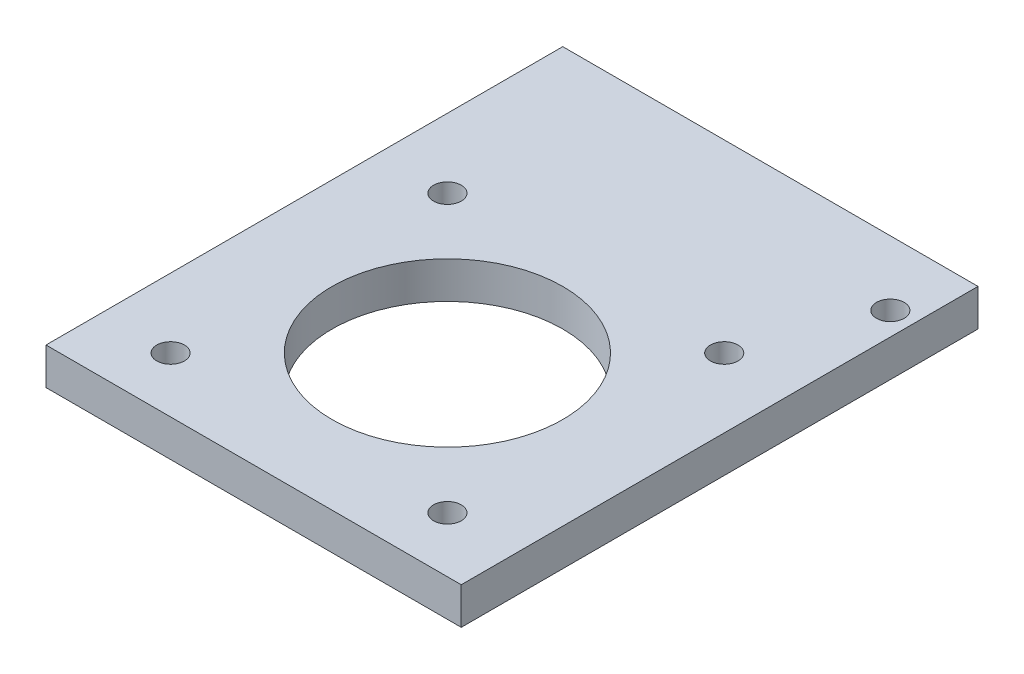
SolidWorks part; units mm, degrees
ref_plane "Plano frontal" through (0, 0, 0) normal (0, 0, 1) x (1, 0, 0)
ref_plane "Plano superior" through (0, 0, 0) normal (0, 1, 0) x (1, 0, 0)
ref_plane "Plano direito" through (0, 0, 0) normal (1, 0, 0) x (0, 0, -1)
sketch "Esboço1" plane through (0, 0, 0) normal (0, 1, 0) x (1, 0, 0)
  line L1 (-22.5, 28) -> (22.5, 28)
  line L2 (-22.5, 28) -> (-22.5, -28)
  line L3 (-22.5, -28) -> (22.5, -28)
  line L4 (22.5, 28) -> (22.5, -28)
  line L5 (-22.5, 28) -> (22.5, -28) construction
  line L6 (-22.5, -28) -> (22.5, 28) construction
  point P0 (0, 0)
  dimension "D1" = 45
  dimension "D2" = 56
extrude "Ressalto-extrusão1" add sketch "Esboço1" along normal blind 4
sketch "Esboço4" plane through (0, 4, 0) normal (0, 1, 0) x (1, 0, 0)
  line L0 (0, 28) -> (0, -7) construction
  line L1 (22.5, 28) -> (-22.5, 28) construction
  line L2 (0, -7) -> (15, -7) construction
  line L3 (15, -7) -> (15, 8) construction
  line L4 (15, 8) -> (-15, 8) construction
  line L5 (-15, 8) -> (-15, -22) construction
  line L6 (-15, -22) -> (15, -22) construction
  line L7 (0, -7) -> (0, 21) construction
  line L8 (0, 21) -> (20, 21) construction
  circle A0 centre (-15, 8) radius 1.5
  circle A1 centre (-15, -22) radius 1.5
  circle A2 centre (15, -22) radius 1.5
  circle A3 centre (15, 8) radius 1.5
  circle A4 centre (20, 21) radius 1.5
  circle A5 centre (0, -7) radius 12.5
  dimension "D7" = 20
  dimension "D8" = 25
  dimension "D1" = 35
  dimension "D2" = 15
  dimension "D3" = 15
  dimension "D4" = 30
  dimension "D5" = 30
  dimension "D6" = 30
extrude "Corte-extrusão1" cut sketch "Esboço4" against normal through all
